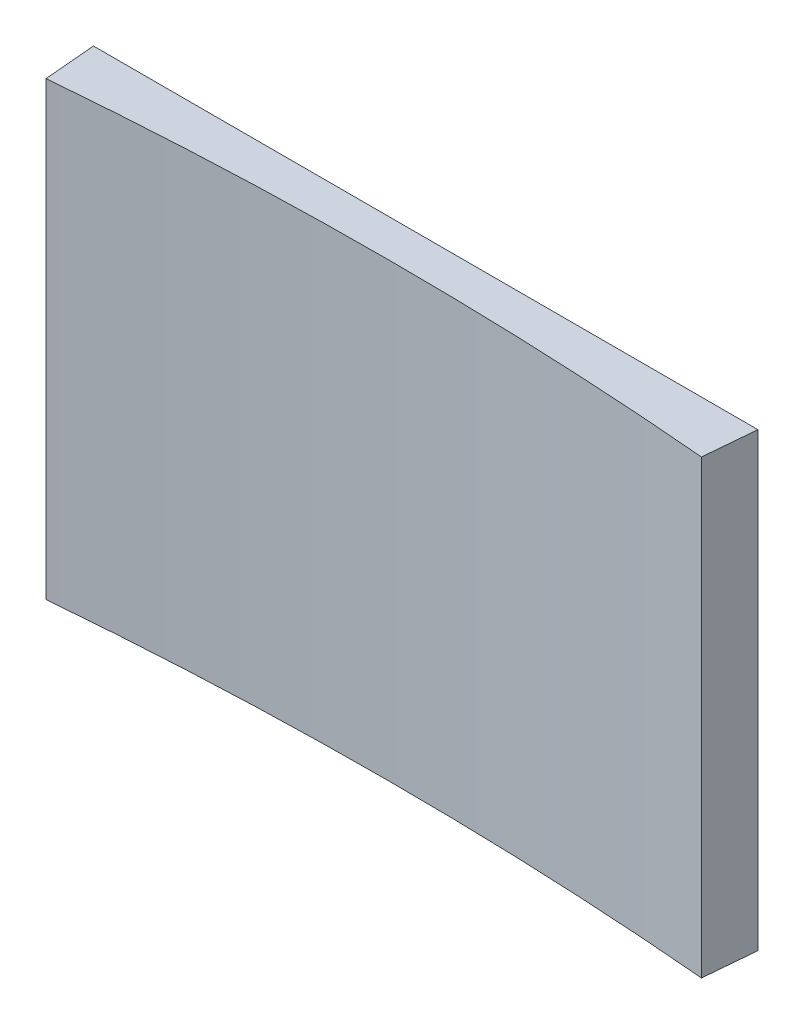
SolidWorks part; units mm, degrees
ref_plane "Front Plane" through (0, 0, 0) normal (0, 0, 1) x (1, 0, 0)
ref_plane "Top Plane" through (0, 0, 0) normal (0, 1, 0) x (1, 0, 0)
ref_plane "Right Plane" through (0, 0, 0) normal (1, 0, 0) x (0, 0, -1)
sketch "Sketch1" plane through (0, 0, 0) normal (0, 1, 0) x (1, 0, 0)
  line L0 (0, 0) -> (0, 66.7257) construction
  line L1 (-4.4182, 50.5) -> (4.4182, 50.5)
  line L2 (4.3578, 49.8097) -> (4.4182, 50.5)
  line L3 (-4.3578, 49.8097) -> (-4.4182, 50.5)
  arc A0 (4.3578, 49.8097) -> (-4.3578, 49.8097) centre (0, 0) ccw
  point P4 (0, 50)
  point P8 (0, 0)
  dimension "D1" = 50
  dimension "D2" = 10
  dimension "D3" = 50.5
  dimension "D4" = 5
  dimension "D5" = 5
extrude "Boss-Extrude1" add sketch "Sketch1" along normal blind 6
